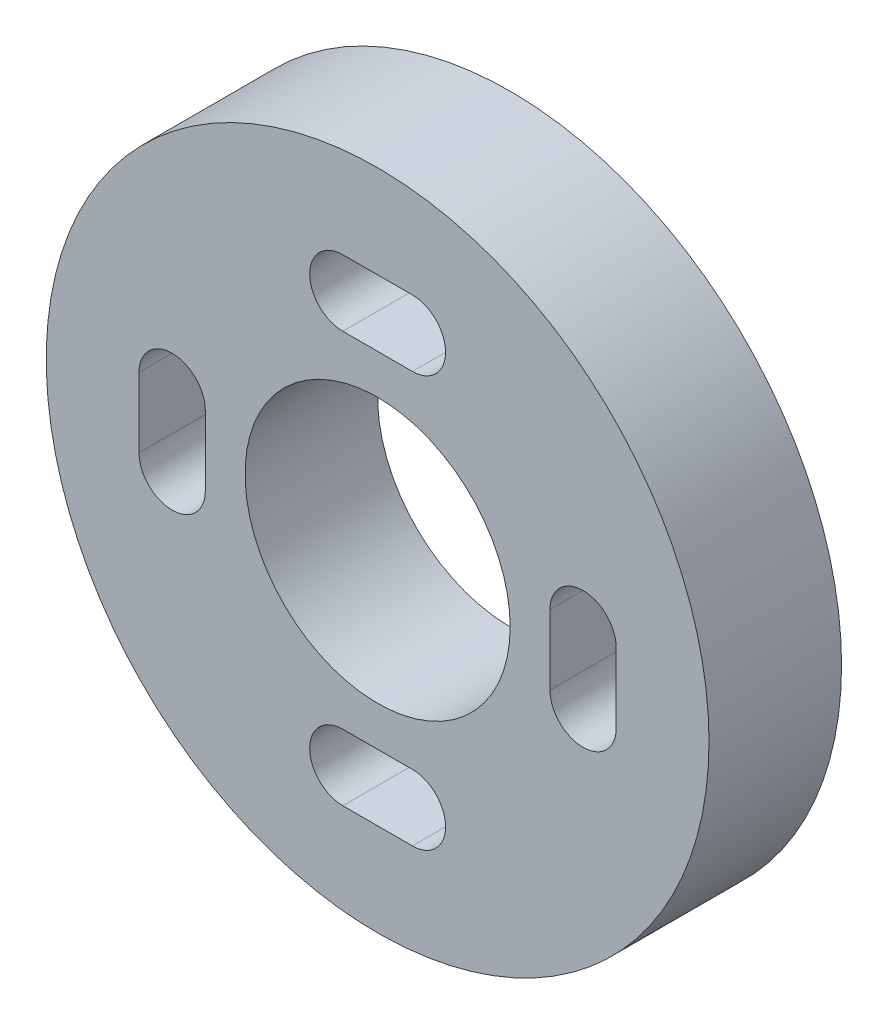
SolidWorks part; units mm, degrees
ref_plane "前基準面" through (0, 0, 0) normal (0, 0, 1) x (1, 0, 0)
ref_plane "上基準面" through (0, 0, 0) normal (0, 1, 0) x (1, 0, 0)
ref_plane "右基準面" through (0, 0, 0) normal (1, 0, 0) x (0, 0, -1)
sketch "草圖1" plane through (0, 0, 0) normal (0, 0, 1) x (1, 0, 0)
  circle A0 centre (0, 0) radius 10
  dimension "D1" = 20
extrude "填料-伸長1" add sketch "草圖1" along normal blind 4
sketch "草圖2" plane through (0, 0, 0) normal (0, 0, 1) x (1, 0, 0)
  line L0 (0, 4.1464) -> (0, -6.1002) construction
  line L1 (-8.1408, 0) -> (8.6618, 0) construction
  line L2 (-1.05, 6.2) -> (1.05, 6.2) construction
  line L3 (-1.05, 7.2) -> (1.05, 7.2)
  line L4 (-1.05, 5.2) -> (1.05, 5.2)
  line L5 (-6.2, 1.05) -> (-6.2, -1.05) construction
  line L6 (-5.2, 1.05) -> (-5.2, -1.05)
  line L7 (-7.2, 1.05) -> (-7.2, -1.05)
  line L8 (6.2, 1.05) -> (6.2, -1.05) construction
  line L9 (5.2, 1.05) -> (5.2, -1.05)
  line L10 (7.2, 1.05) -> (7.2, -1.05)
  line L11 (-1.05, -6.2) -> (1.05, -6.2) construction
  line L12 (-1.05, -7.2) -> (1.05, -7.2)
  line L13 (-1.05, -5.2) -> (1.05, -5.2)
  circle A0 centre (0, 0) radius 4
  arc A1 (-1.05, 7.2) -> (-1.05, 5.2) centre (-1.05, 6.2) ccw
  arc A2 (1.05, 5.2) -> (1.05, 7.2) centre (1.05, 6.2) ccw
  arc A3 (-5.2, 1.05) -> (-7.2, 1.05) centre (-6.2, 1.05) ccw
  arc A4 (-7.2, -1.05) -> (-5.2, -1.05) centre (-6.2, -1.05) ccw
  arc A5 (5.2, 1.05) -> (7.2, 1.05) centre (6.2, 1.05) cw
  arc A6 (7.2, -1.05) -> (5.2, -1.05) centre (6.2, -1.05) cw
  arc A7 (-1.05, -7.2) -> (-1.05, -5.2) centre (-1.05, -6.2) cw
  arc A8 (1.05, -5.2) -> (1.05, -7.2) centre (1.05, -6.2) cw
  point P9 (0, 6.2)
  point P14 (-6.2, 0)
  point P23 (6.2, 0)
  point P30 (0, -6.2)
  dimension "D1" = 8
  dimension "D2" = 2.1
  dimension "D3" = 1.05
  dimension "D4" = 2
  dimension "D5" = 2
  dimension "D6" = 2.1
  dimension "D7" = 1.05
  dimension "D8" = 6.2
  dimension "D9" = 6.2
extrude "除料-伸長1" cut sketch "草圖2" along normal blind 4
